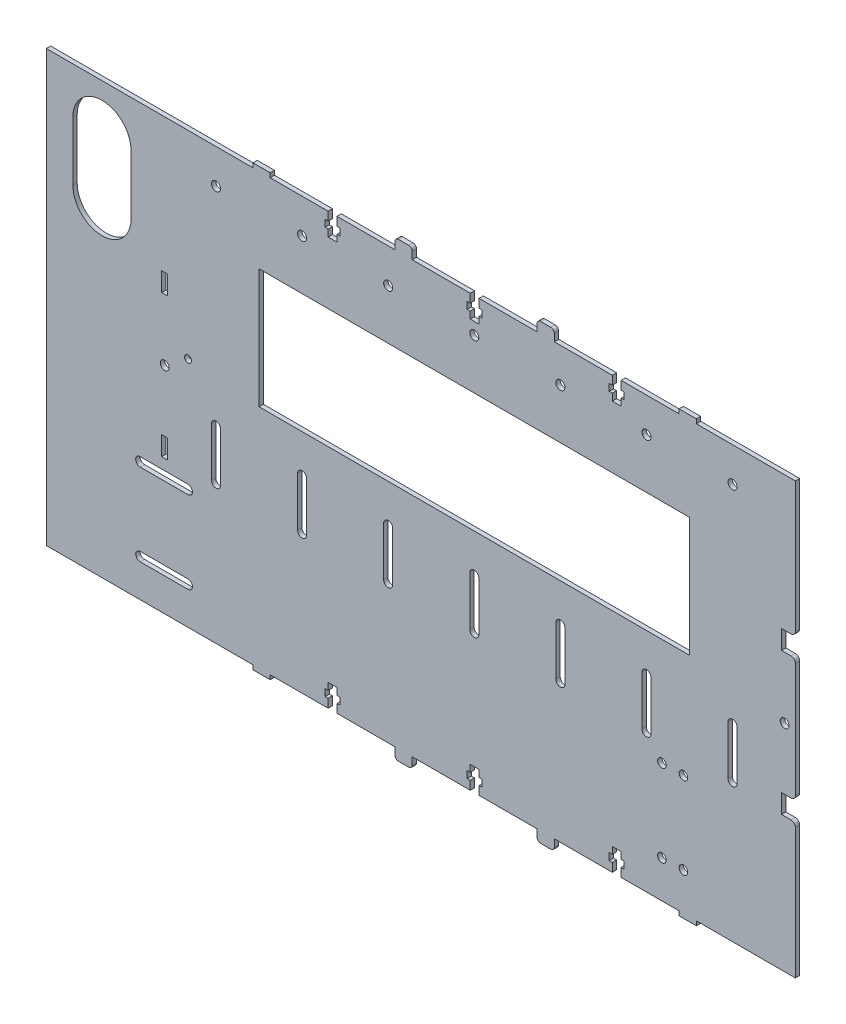
SolidWorks part; units mm, degrees
ref_plane "前视基准面" through (0, 0, 0) normal (0, 0, 1) x (1, 0, 0)
ref_plane "上视基准面" through (0, 0, 0) normal (0, 1, 0) x (1, 0, 0)
ref_plane "右视基准面" through (0, 0, 0) normal (1, 0, 0) x (0, 0, -1)
sketch "草图1" plane through (0, 0, 0) normal (0, 0, 1) x (1, 0, 0)
  line L0 (0, 0) -> (0, -4)
  line L1 (0, -4) -> (-1.45, -4)
  line L2 (-1.45, -4) -> (-1.45, -7.2)
  line L3 (-1.45, -7.2) -> (0, -7.2)
  line L4 (0, -7.2) -> (0, -10.4)
  line L5 (0, -10.4) -> (4.1, -10.4)
  line L6 (4.1, -10.4) -> (4.1, -7.2)
  line L7 (4.1, -7.2) -> (5.55, -7.2)
  line L8 (5.55, -7.2) -> (5.55, -4)
  line L9 (5.55, -4) -> (4.1, -4)
  line L10 (4.1, -4) -> (4.1, 0)
  line L11 (0, 0) -> (-26.95, 0)
  line L12 (-26.95, 0) -> (-26.95, 5)
  line L13 (-26.95, 5) -> (-34.95, 5)
  line L14 (-34.95, 5) -> (-34.95, 0)
  line L15 (2.05, -10.4) -> (2.05, -56.6) construction
  line L16 (-30.95, 5) -> (-30.95, 0) construction
  line L17 (-67.45, -4) -> (-66, -4)
  line L18 (-66, -7.2) -> (-67.45, -7.2)
  line L19 (-60.45, -7.2) -> (-61.9, -7.2)
  line L20 (-61.9, -4) -> (-60.45, -4)
  line L21 (-66, -4) -> (-66, 0)
  line L22 (-66, -10.4) -> (-66, -7.2)
  line L23 (-61.9, -10.4) -> (-66, -10.4)
  line L24 (-61.9, -7.2) -> (-61.9, -10.4)
  line L25 (-67.45, -7.2) -> (-67.45, -4)
  line L26 (-60.45, -4) -> (-60.45, -7.2)
  line L27 (-61.9, 0) -> (-61.9, -4)
  line L28 (-61.9, 0) -> (-34.95, 0)
  line L29 (31.05, 5) -> (39.05, 5)
  line L30 (31.05, 0) -> (31.05, 5)
  line L31 (39.05, 5) -> (39.05, 0)
  line L32 (4.1, 0) -> (31.05, 0)
  line L33 (66, 0) -> (39.05, 0)
  line L34 (66, 0) -> (66, -4)
  line L35 (64.55, -4) -> (64.55, -7.2)
  line L36 (71.55, -7.2) -> (71.55, -4)
  line L37 (66, -7.2) -> (66, -10.4)
  line L38 (66, -10.4) -> (70.1, -10.4)
  line L39 (70.1, -10.4) -> (70.1, -7.2)
  line L40 (70.1, -4) -> (70.1, 0)
  line L41 (66, -4) -> (64.55, -4)
  line L42 (64.55, -7.2) -> (66, -7.2)
  line L43 (70.1, -7.2) -> (71.55, -7.2)
  line L44 (71.55, -4) -> (70.1, -4)
  line L45 (68.05, -10.4) -> (68.05, -6.6) construction
  line L46 (70.1, 0) -> (97.05, 0)
  line L47 (132, 0) -> (105.05, 0)
  line L48 (97.05, 5) -> (97.05, 0)
  line L49 (105.05, 0) -> (105.05, 5)
  line L50 (105.05, 5) -> (97.05, 5)
  line L51 (-63.95, -10.4) -> (-63.95, -6.6) construction
  line L52 (-96.95, 5) -> (-96.95, 0) construction
  line L53 (-66, 0) -> (-92.95, 0)
  line L54 (-92.95, 5) -> (-92.95, 0)
  line L55 (-100.95, 5) -> (-92.95, 5)
  line L56 (-100.95, 0) -> (-100.95, 5)
  line L57 (-127.9, 0) -> (-100.95, 0)
  line L58 (2.05, -10.4) -> (-140.5, -10.4) construction
  line L59 (-127.9, 0) -> (-139.95, 0)
  line L60 (132, 0) -> (144.05, 0)
  line L64 (-139.95, 0) -> (-141.95, 0)
  line L66 (-96.95, -205) -> (-96.95, -200) construction
  line L79 (-63.95, -189.6) -> (-63.95, -193.4) construction
  line L101 (68.05, -189.6) -> (68.05, -193.4) construction
  line L102 (-30.95, -205) -> (-30.95, -200) construction
  line L103 (-127.9, -200) -> (-100.95, -200)
  line L104 (-100.95, -200) -> (-100.95, -205)
  line L137 (-141.95, 0) -> (-141.95, -200) construction
  line L138 (-141.95, -200) -> (-139.95, -200)
  line L140 (-143.35, -62.6) -> (-140.55, -62.6)
  line L141 (-143.35, -62.6) -> (-143.35, -71.4)
  line L142 (-143.35, -71.4) -> (-140.55, -71.4)
  line L143 (-140.55, -62.6) -> (-140.55, -71.4)
  line L144 (-143.35, -62.6) -> (-140.55, -71.4) construction
  line L145 (-143.35, -71.4) -> (-140.55, -62.6) construction
  line L146 (-141.95, -100) -> (-134.9383, -100) construction
  line L148 (-140.55, -137.4) -> (-140.55, -128.6)
  line L149 (-143.35, -137.4) -> (-143.35, -128.6)
  line L150 (-143.35, -128.6) -> (-140.55, -128.6)
  line L151 (-143.35, -137.4) -> (-140.55, -137.4)
  line L152 (-141.95, 0) -> (-146.95, 0)
  line L154 (-146.95, -200) -> (-141.95, -200)
  line L156 (146.05, -200) -> (144.05, -200)
  line L157 (151.05, -200) -> (146.05, -200)
  line L158 (144.05, 0) -> (146.05, 0)
  line L159 (146.05, 0) -> (151.05, 0)
  line L160 (151.05, 0) -> (151.05, -200)
  line L161 (146.05, -100) -> (139.0383, -100) construction
  line L162 (147.45, -71.4) -> (144.65, -62.6) construction
  line L163 (147.45, -62.6) -> (144.65, -71.4) construction
  line L164 (146.05, 0) -> (146.05, -200) construction
  line L165 (147.45, -137.4) -> (144.65, -137.4)
  line L166 (147.45, -128.6) -> (144.65, -128.6)
  line L167 (147.45, -137.4) -> (147.45, -128.6)
  line L168 (144.65, -137.4) -> (144.65, -128.6)
  line L169 (144.65, -62.6) -> (144.65, -71.4)
  line L170 (147.45, -71.4) -> (144.65, -71.4)
  line L171 (147.45, -62.6) -> (147.45, -71.4)
  line L172 (147.45, -62.6) -> (144.65, -62.6)
  line L173 (-100.95, -205) -> (-92.95, -205)
  line L174 (-92.95, -205) -> (-92.95, -200)
  line L175 (-66, -200) -> (-92.95, -200)
  line L176 (105.05, -205) -> (97.05, -205)
  line L177 (105.05, -200) -> (105.05, -205)
  line L178 (97.05, -205) -> (97.05, -200)
  line L179 (132, -200) -> (105.05, -200)
  line L180 (70.1, -200) -> (97.05, -200)
  line L181 (71.55, -196) -> (70.1, -196)
  line L182 (70.1, -192.8) -> (71.55, -192.8)
  line L183 (64.55, -192.8) -> (66, -192.8)
  line L184 (66, -196) -> (64.55, -196)
  line L185 (70.1, -196) -> (70.1, -200)
  line L186 (70.1, -189.6) -> (70.1, -192.8)
  line L187 (66, -189.6) -> (70.1, -189.6)
  line L188 (66, -192.8) -> (66, -189.6)
  line L189 (71.55, -192.8) -> (71.55, -196)
  line L190 (64.55, -196) -> (64.55, -192.8)
  line L191 (66, -200) -> (66, -196)
  line L192 (66, -200) -> (39.05, -200)
  line L193 (4.1, -200) -> (31.05, -200)
  line L194 (39.05, -205) -> (39.05, -200)
  line L195 (31.05, -200) -> (31.05, -205)
  line L196 (31.05, -205) -> (39.05, -205)
  line L197 (-61.9, -200) -> (-34.95, -200)
  line L198 (-61.9, -200) -> (-61.9, -196)
  line L199 (-60.45, -196) -> (-60.45, -192.8)
  line L200 (-67.45, -192.8) -> (-67.45, -196)
  line L201 (-61.9, -192.8) -> (-61.9, -189.6)
  line L202 (-61.9, -189.6) -> (-66, -189.6)
  line L203 (-66, -189.6) -> (-66, -192.8)
  line L204 (-66, -196) -> (-66, -200)
  line L205 (-61.9, -196) -> (-60.45, -196)
  line L206 (-60.45, -192.8) -> (-61.9, -192.8)
  line L207 (-66, -192.8) -> (-67.45, -192.8)
  line L208 (-67.45, -196) -> (-66, -196)
  line L209 (-34.95, -205) -> (-34.95, -200)
  line L210 (-26.95, -205) -> (-34.95, -205)
  line L211 (-26.95, -200) -> (-26.95, -205)
  line L212 (0, -200) -> (-26.95, -200)
  line L213 (4.1, -196) -> (4.1, -200)
  line L214 (5.55, -196) -> (4.1, -196)
  line L215 (5.55, -192.8) -> (5.55, -196)
  line L216 (4.1, -192.8) -> (5.55, -192.8)
  line L217 (4.1, -189.6) -> (4.1, -192.8)
  line L218 (0, -189.6) -> (4.1, -189.6)
  line L219 (0, -192.8) -> (0, -189.6)
  line L220 (-1.45, -192.8) -> (0, -192.8)
  line L221 (-1.45, -196) -> (-1.45, -192.8)
  line L222 (0, -196) -> (-1.45, -196)
  line L223 (0, -200) -> (0, -196)
  line L224 (-139.95, -200) -> (-127.9, -200)
  line L225 (132, -200) -> (144.05, -200)
  line L226 (-38.121, 0.7643) -> (-38.121, -54.2997) construction
  line L227 (-104.121, 0.7643) -> (-104.121, -54.2997) construction
  line L228 (137.879, -104.2357) -> (107.9873, -104.2357) construction
  line L229 (-104.121, -209.2357) -> (-104.121, -154.1717) construction
  line L230 (-38.121, -209.2357) -> (-38.121, -154.1717) construction
  line L231 (-78.121, -135.4214) -> (-78.121, -112.5786) construction
  line L232 (-80.221, -135.4214) -> (-80.221, -112.5786)
  line L233 (-76.021, -135.4214) -> (-76.021, -112.5786)
  line L234 (-38.121, -135.4214) -> (-38.121, -112.5786) construction
  line L235 (-98.121, -39.2357) -> (-98.121, -94.7357)
  line L236 (-98.121, -94.7357) -> (101.879, -94.7357)
  line L237 (-118.121, -135.4214) -> (-118.121, -112.5786) construction
  line L238 (-120.221, -135.4214) -> (-120.221, -112.5786)
  line L239 (-116.021, -135.4214) -> (-116.021, -112.5786)
  line L240 (-40.221, -135.4214) -> (-40.221, -112.5786)
  line L243 (-36.021, -135.4214) -> (-36.021, -112.5786)
  line L246 (1.879, -135.4214) -> (1.879, -112.5786) construction
  line L249 (-0.221, -135.4214) -> (-0.221, -112.5786)
  line L252 (3.979, -135.4214) -> (3.979, -112.5786)
  line L255 (101.879, -39.2357) -> (101.879, -94.7357)
  line L256 (-118.121, -16) -> (121.879, -16) construction
  line L257 (-118.121, -16) -> (-118.121, -111.5) construction
  line L258 (-118.121, -111.5) -> (121.879, -111.5) construction
  line L259 (-98.121, -39.2357) -> (101.879, -39.2357)
  line L260 (41.879, -135.4214) -> (41.879, -112.5786) construction
  line L261 (39.779, -135.4214) -> (39.779, -112.5786)
  line L262 (43.979, -135.4214) -> (43.979, -112.5786)
  line L263 (81.879, -135.4214) -> (81.879, -112.5786) construction
  line L264 (79.779, -135.4214) -> (79.779, -112.5786)
  line L265 (83.979, -135.4214) -> (83.979, -112.5786)
  line L266 (121.879, -135.4214) -> (121.879, -112.5786) construction
  line L267 (119.779, -135.4214) -> (119.779, -112.5786)
  line L268 (123.979, -135.4214) -> (123.979, -112.5786)
  line L269 (-171.1058, -21.4111) -> (-171.1058, -48.8744) construction
  line L270 (-146.95, 0) -> (-196.95, 0)
  line L271 (-146.95, 0) -> (-146.95, -200) construction
  line L272 (99.05, -182.5174) -> (99.05, -144.5174) construction
  line L273 (99.05, -144.5174) -> (89.05, -144.5174) construction
  line L274 (94.05, -144.5174) -> (94.05, -152.7968) construction
  line L275 (94.05, -152.7968) -> (-142.25, -152.7968) construction
  line L276 (-24.1, -152.7968) -> (-24.1, -162.5312) construction
  line L277 (-139.95, -200) -> (151.05, -200) construction
  line L278 (-153.3224, -144.5174) -> (-131.1776, -144.5174) construction
  line L279 (-153.3224, -142.4174) -> (-131.1776, -142.4174)
  line L280 (-153.3224, -146.6174) -> (-131.1776, -146.6174)
  line L281 (-153.3224, -182.627) -> (-131.1776, -182.627) construction
  line L282 (-153.3224, -180.527) -> (-131.1776, -180.527)
  line L283 (-153.3224, -184.727) -> (-131.1776, -184.727)
  line L284 (-146.95, -200) -> (-196.95, -200)
  line L285 (-196.95, 0) -> (-196.95, -200)
  line L286 (-157.5922, -21.4111) -> (-157.5922, -48.8744)
  line L287 (-184.6194, -21.4111) -> (-184.6194, -48.8744)
  circle A0 centre (-141.95, -100) radius 2.05
  circle A1 centre (146.05, -100) radius 2.05
  circle A3 centre (-118.121, -16) radius 2.1
  circle A4 centre (-78.121, -16) radius 2.1
  circle A5 centre (-38.121, -16) radius 2.1
  circle A6 centre (1.879, -16) radius 2.1
  circle A7 centre (41.879, -16) radius 2.1
  circle A8 centre (81.879, -16) radius 2.1
  arc A9 (-120.221, -135.4214) -> (-116.021, -135.4214) centre (-118.121, -135.4214) ccw
  arc A10 (-116.021, -112.5786) -> (-120.221, -112.5786) centre (-118.121, -112.5786) ccw
  circle A21 centre (99.05, -182.5174) radius 2
  circle A22 centre (99.05, -144.5174) radius 2
  circle A23 centre (89.05, -144.5174) radius 2
  circle A24 centre (89.0506, -182.627) radius 2
  circle A25 centre (-147.25, -182.5174) radius 2 construction
  circle A26 centre (-137.2506, -182.627) radius 2 construction
  circle A27 centre (-137.25, -144.5174) radius 2 construction
  circle A28 centre (-147.25, -144.5174) radius 2 construction
  arc A29 (-153.3224, -142.4174) -> (-153.3224, -146.6174) centre (-153.3224, -144.5174) ccw
  arc A30 (-131.1776, -146.6174) -> (-131.1776, -142.4174) centre (-131.1776, -144.5174) ccw
  arc A31 (-153.3224, -180.527) -> (-153.3224, -184.727) centre (-153.3224, -182.627) ccw
  arc A32 (-131.1776, -184.727) -> (-131.1776, -180.527) centre (-131.1776, -182.627) ccw
  arc A33 (-80.221, -135.4214) -> (-76.021, -135.4214) centre (-78.121, -135.4214) ccw
  arc A34 (-76.021, -112.5786) -> (-80.221, -112.5786) centre (-78.121, -112.5786) ccw
  arc A35 (-40.221, -135.4214) -> (-36.021, -135.4214) centre (-38.121, -135.4214) ccw
  arc A36 (-36.021, -112.5786) -> (-40.221, -112.5786) centre (-38.121, -112.5786) ccw
  arc A37 (-0.221, -135.4214) -> (3.979, -135.4214) centre (1.879, -135.4214) ccw
  arc A38 (3.979, -112.5786) -> (-0.221, -112.5786) centre (1.879, -112.5786) ccw
  arc A39 (39.779, -135.4214) -> (43.979, -135.4214) centre (41.879, -135.4214) ccw
  arc A40 (43.979, -112.5786) -> (39.779, -112.5786) centre (41.879, -112.5786) ccw
  arc A41 (79.779, -135.4214) -> (83.979, -135.4214) centre (81.879, -135.4214) ccw
  arc A42 (83.979, -112.5786) -> (79.779, -112.5786) centre (81.879, -112.5786) ccw
  circle A43 centre (121.879, -16) radius 2.1
  arc A44 (119.779, -135.4214) -> (123.979, -135.4214) centre (121.879, -135.4214) ccw
  arc A45 (123.979, -112.5786) -> (119.779, -112.5786) centre (121.879, -112.5786) ccw
  circle A46 centre (-131.1232, -92.0123) radius 1.5966
  arc A49 (-157.5922, -21.4111) -> (-184.6194, -21.4111) centre (-171.1058, -21.4111) ccw
  arc A50 (-184.6194, -48.8744) -> (-157.5922, -48.8744) centre (-171.1058, -48.8744) ccw
  point P139 (-141.95, -67)
  point P166 (146.05, -67)
  point P178 (-78.121, -124)
  point P200 (-118.121, -124)
  point P209 (-38.121, -124)
  point P216 (1.879, -124)
  point P223 (41.879, -124)
  point P230 (81.879, -124)
  point P237 (121.879, -124)
  point P249 (-171.1058, -35.1427)
  point P282 (-142.25, -144.5174)
  point P288 (-142.25, -182.627)
  dimension "D9" = 33
  dimension "D14" = 33
  dimension "D5" = 8
  dimension "D24" = 50
  dimension "D1" = 4.1
  dimension "D2" = 7
  dimension "D3" = 4
  dimension "D4" = 3.2
  dimension "D6" = 200
  dimension "D7" = 5
  dimension "D8" = 284
  dimension "D10" = 2.8
  dimension "D11" = 2
  dimension "D12" = 8.8
  dimension "D13" = 5
  dimension "D15" = 40
  dimension "D16" = 40
  dimension "D17" = 40
  dimension "D18" = 40
  dimension "D19" = 40
  dimension "D20" = 40
  dimension "D21" = 108
  dimension "D22" = 16
  dimension "D23" = 7
extrude "凸台-拉伸1" add sketch "草图1" along normal blind 2 contours L179 L225 L156 L157 L160 L159 L158 L60 L47 L49 L50 L48 L46 L40 L44 L36 L43 L39 L38 L37 L42 L35 L41 L34 L33 L31 L29 L30 L32 L10 L9 L8 L7 L6 L5 L4 L3 L2 L1 L0 L11 L12 L13 L14 L28 L27 L20 L26 L19 L24 L23
sketch "草图2" plane through (0, 0, 0) normal (0, 1, 0) x (1, 0, 0)
  line L0 (-66, -1) -> (-61.9, -1)
  line L1 (-66, -2) -> (-66, 0) construction
  line L2 (-61.9, -2) -> (-61.9, 0) construction
  circle A0 centre (-63.95, -1) radius 2.05
sketch "草图3" plane through (0, -200, 0) normal (0, -1, 0) x (1, 0, 0)
  line L0 (-66, 1) -> (-61.9, 1)
  line L1 (-66, 2) -> (-66, 0) construction
  line L2 (-61.9, 2) -> (-61.9, 0) construction
  circle A0 centre (-63.95, 1) radius 2.05
sketch "草图4" plane through (0, 0, 2) normal (0, 0, 1) x (1, 0, 0)
  line L0 (-66, 0) -> (-92.95, 0) construction
  line L1 (90.1394, 11.0656) -> (110.8448, 11.0656)
  line L2 (90.1394, 11.0656) -> (90.1394, 2)
  line L3 (90.1394, 2) -> (110.8448, 2)
  line L4 (110.8448, 11.0656) -> (110.8448, 2)
  line L5 (129.0593, -220.504) -> (87.0868, -220.504)
  line L6 (129.0593, -220.504) -> (129.0593, -202)
  line L7 (129.0593, -202) -> (87.0868, -202)
  line L8 (87.0868, -220.504) -> (87.0868, -202)
  line L9 (-74.9592, -217.0386) -> (-125.8159, -217.0386)
  line L10 (-74.9592, -217.0386) -> (-74.9592, -202)
  line L11 (-74.9592, -202) -> (-125.8159, -202)
  line L12 (-125.8159, -217.0386) -> (-125.8159, -202)
  line L13 (-125.8159, 16.3207) -> (-86.3602, 16.3207)
  line L14 (-125.8159, 16.3207) -> (-125.8159, 2)
  line L15 (-125.8159, 2) -> (-86.3602, 2)
  line L16 (-86.3602, 16.3207) -> (-86.3602, 2)
  line L17 (132, 0) -> (105.05, 0) construction
  line L18 (132, -200) -> (105.05, -200) construction
  line L19 (-127.9, -200) -> (-100.95, -200) construction
  dimension "D1" = 2
  dimension "D2" = 2
  dimension "D3" = 2
  dimension "D4" = 2
extrude "切除-拉伸1" cut sketch "草图4" against normal blind 2
fillet "圆角1" radius 1.6 8 edges at (39.05, 5, 1) (31.05, 5, 1) (-26.95, 5, 1) (-34.95, 5, 1) (39.05, -205, 1) (31.05, -205, 1) (-26.95, -205, 1) (-34.95, -205, 1)
sketch "草图5" plane through (0, 0, 2) normal (0, 0, 1) x (1, 0, 0)
  line L1 (147.45, -62.6) -> (155.2195, -62.6)
  line L2 (147.45, -62.6) -> (147.45, -71.4)
  line L3 (147.45, -71.4) -> (155.2195, -71.4)
  line L4 (155.2195, -62.6) -> (155.2195, -71.4)
  line L5 (147.45, -128.6) -> (158.737, -128.6)
  line L6 (147.45, -128.6) -> (147.45, -137.4)
  line L7 (147.45, -137.4) -> (158.737, -137.4)
  line L8 (158.737, -128.6) -> (158.737, -137.4)
extrude "切除-拉伸2" cut sketch "草图5" against normal blind 2
fillet "圆角2" radius 2 4 edges at (151.05, -137.4, 1) (151.05, -128.6, 1) (151.05, -71.4, 1) (151.05, -62.6, 1)
